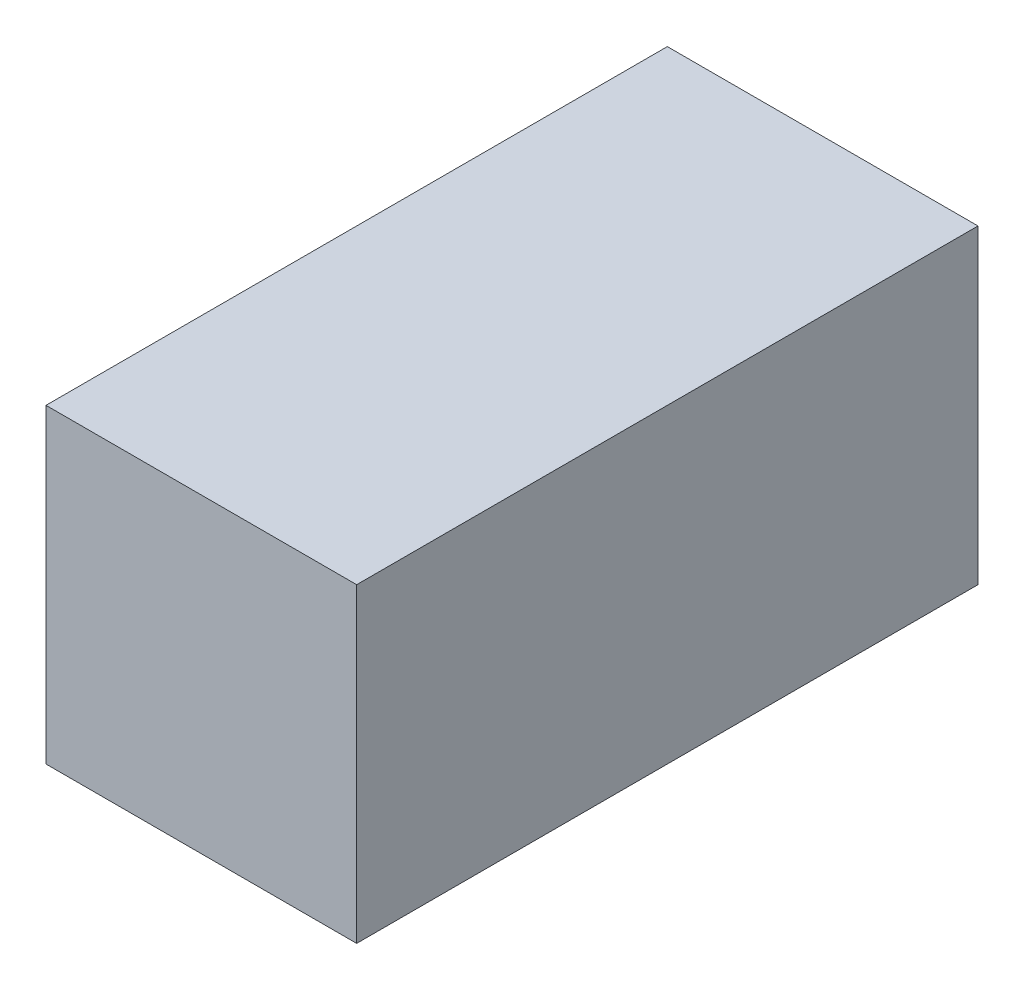
SolidWorks part; units mm, degrees
ref_plane "Front Plane" through (0, 0, 0) normal (0, 0, 1) x (1, 0, 0)
ref_plane "Top Plane" through (0, 0, 0) normal (0, 1, 0) x (1, 0, 0)
ref_plane "Right Plane" through (0, 0, 0) normal (1, 0, 0) x (0, 0, -1)
other "Configuration Table"
sketch "Sketch1" plane through (0, 0, 0) normal (0, 0, 1) x (1, 0, 0)
  line L1 (0, 0) -> (25.4, 0)
  line L2 (0, 0) -> (0, 25.4)
  line L3 (0, 25.4) -> (25.4, 25.4)
  line L4 (25.4, 0) -> (25.4, 25.4)
  dimension "D1" = 25.4
  dimension "D2" = 25.4
extrude "Extrude1" add sketch "Sketch1" along normal blind 50.8
